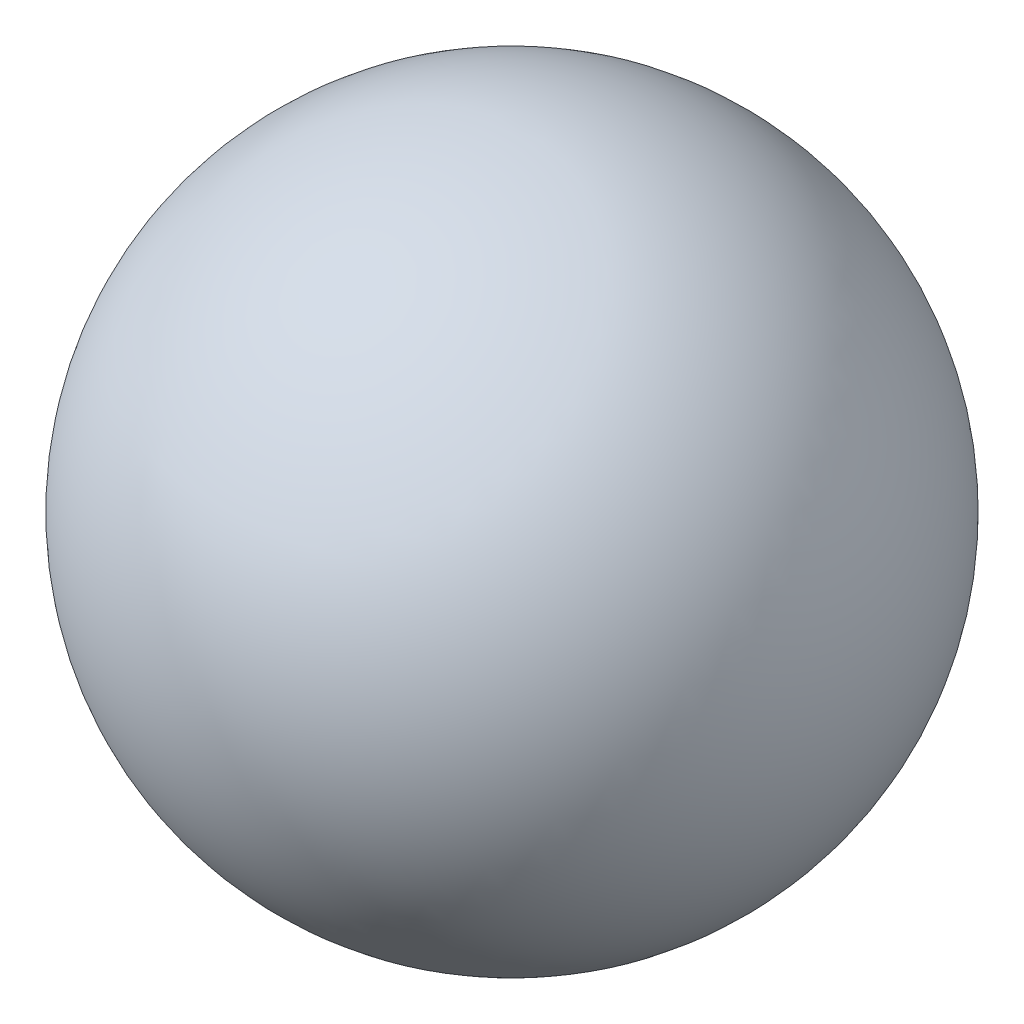
SolidWorks part; units mm, degrees
ref_plane "Front Plane" through (0, 0, 0) normal (0, 0, 1) x (1, 0, 0)
ref_plane "Top Plane" through (0, 0, 0) normal (0, 1, 0) x (1, 0, 0)
ref_plane "Right Plane" through (0, 0, 0) normal (1, 0, 0) x (0, 0, -1)
sketch "Sketch1" plane through (0, 0, 0) normal (0, 0, 1) x (1, 0, 0)
  line L0 (0, -17.2724) -> (0, 20.5649) construction
  circle A0 centre (0, 0) radius 37.5
  point P4 (0, 0)
  point P6 (0, 0)
  dimension "D1" = 75
revolve "Revolve5" add sketch "Sketch1" angle 360 mid plane about L0
